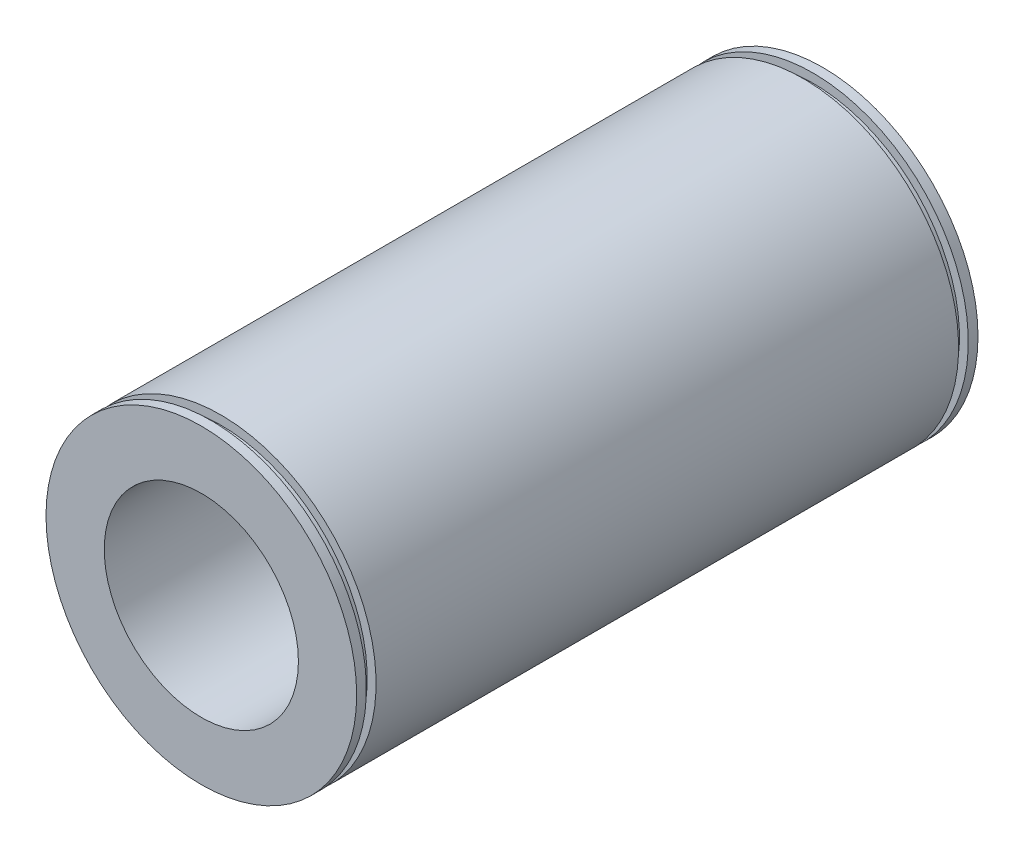
SolidWorks part; units mm, degrees
ref_plane "Front Plane" through (0, 0, 0) normal (0, 0, 1) x (1, 0, 0)
ref_plane "Top Plane" through (0, 0, 0) normal (0, 1, 0) x (1, 0, 0)
ref_plane "Right Plane" through (0, 0, 0) normal (1, 0, 0) x (0, 0, -1)
sketch "Sketch1" plane through (0, 0, 0) normal (0, 0, 1) x (1, 0, 0)
  circle A0 centre (0, 0) radius 25.4
  circle A1 centre (0, 0) radius 15.875
  circle A2 centre (0, 0) radius 23.9522 construction
  point P6 (0, 23.9522)
  dimension "D1" = 50.8
  dimension "D2" = 31.75
  dimension "D3" = 47.9044
extrude "Boss-Extrude1" add sketch "Sketch1" along normal mid plane 101.6
sketch "Sketch2" plane through (0, 0, 0) normal (1, 0, 0) x (0, 0, -1)
  line L0 (-50.8, 25.4) -> (-50.8, -25.4) construction
  line L1 (-49.2125, 25.4) -> (-47.625, 25.4)
  line L2 (-49.2125, 25.4) -> (-49.2125, 23.9522)
  line L3 (-49.2125, 23.9522) -> (-47.625, 23.9522)
  line L4 (-47.625, 25.4) -> (-47.625, 23.9522)
  line L5 (0, 23.9522) -> (0, -23.9522) construction
  line L6 (0, 0) -> (-75.0133, 0) construction
  line L9 (-50.8, 23.9522) -> (0, 23.9522) construction
  dimension "D1" = 1.5875
  dimension "D2" = 1.5875
  dimension "D4" = 25.4
revolve "Cut-Revolve1" cut sketch "Sketch2" angle 360 about L6
mirror "Mirror1" about plane through (0, 0, 0) normal (0, 0, 1) of "Cut-Revolve1"
